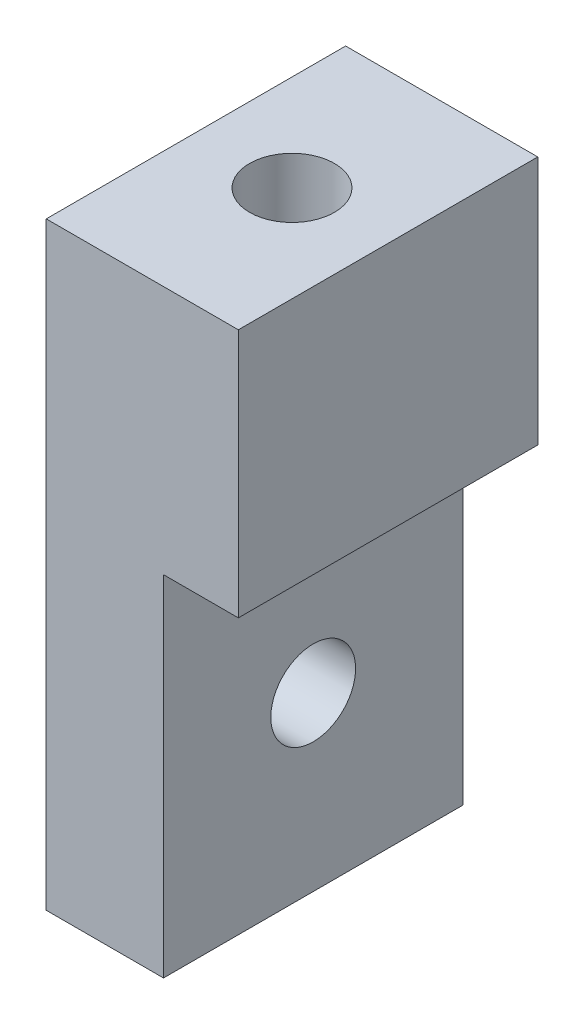
SolidWorks part; units mm, degrees
ref_plane "Front Plane" through (0, 0, 0) normal (0, 0, 1) x (1, 0, 0)
ref_plane "Top Plane" through (0, 0, 0) normal (0, 1, 0) x (1, 0, 0)
ref_plane "Right Plane" through (0, 0, 0) normal (1, 0, 0) x (0, 0, -1)
sketch "Sketch1" plane through (0, 0, 0) normal (0, 0, 1) x (1, 0, 0)
  line L0 (0.425, -6) -> (0.425, 1)
  line L1 (-1.925, 6) -> (1.925, 6)
  line L2 (-1.925, 6) -> (-1.925, -6)
  line L3 (-1.925, -6) -> (1.925, -6)
  line L4 (1.925, 6) -> (1.925, -6)
  line L5 (-1.925, 6) -> (1.925, -6) construction
  line L6 (-1.925, -6) -> (1.925, 6) construction
  line L7 (0.425, 1) -> (1.925, 1)
  line L8 (1.925, 1) -> (1.925, -6)
  point P0 (0, 0)
  dimension "D1" = 0
  dimension "D2" = 12
  dimension "D3" = 1.5
  dimension "D4" = 2.35
  dimension "D5" = 3.85
  dimension "D6" = 5
extrude "Boss-Extrude1" add sketch "Sketch1" along normal blind 6 contours L7 L8 L3 L4 L1 L2 L0
sketch "Sketch2" plane through (-1.925, 0, 0) normal (-1, 0, 0) x (0, 0, 1)
  line L0 (3, 0.8973) -> (3, -6) construction
  line L2 (6, -2.5513) -> (0, -2.5513) construction
  line L3 (0, 6) -> (0, -6) construction
  line L5 (6, -6) -> (0, -6)
  line L6 (6, -6) -> (6, 0.8973)
  line L7 (6, 0.8973) -> (0, 0.8973)
  line L8 (0, -6) -> (0, 0.8973)
  circle A0 centre (3, -2.5513) radius 0.85
  dimension "D1" = 1.7
  dimension "D2" = 3.4487
extrude "Cut-Extrude1" cut sketch "Sketch2" against normal through all contours A0
sketch "Sketch3" plane through (0, 6, 0) normal (0, 1, 0) x (1, 0, 0)
  line L0 (1.925, -6) -> (1.925, 0) construction
  line L1 (0.275, -6) -> (0.275, 0) construction
  line L2 (-1.925, -6) -> (1.925, -6) construction
  line L3 (-1.925, -3) -> (1.925, -3) construction
  line L4 (-1.925, -6) -> (-1.925, 0) construction
  line L5 (1.925, -6) -> (-1.375, -6) construction
  line L6 (-1.925, 0) -> (1.925, 0) construction
  line L7 (0, 0) -> (0, -6) construction
  circle A0 centre (0, -3) radius 0.85
  dimension "D1" = 1.7
  dimension "D2" = 3.3
extrude "Cut-Extrude2" cut sketch "Sketch3" against normal up to surface (5 mm away) up to face at (1.175, 1, 3)
